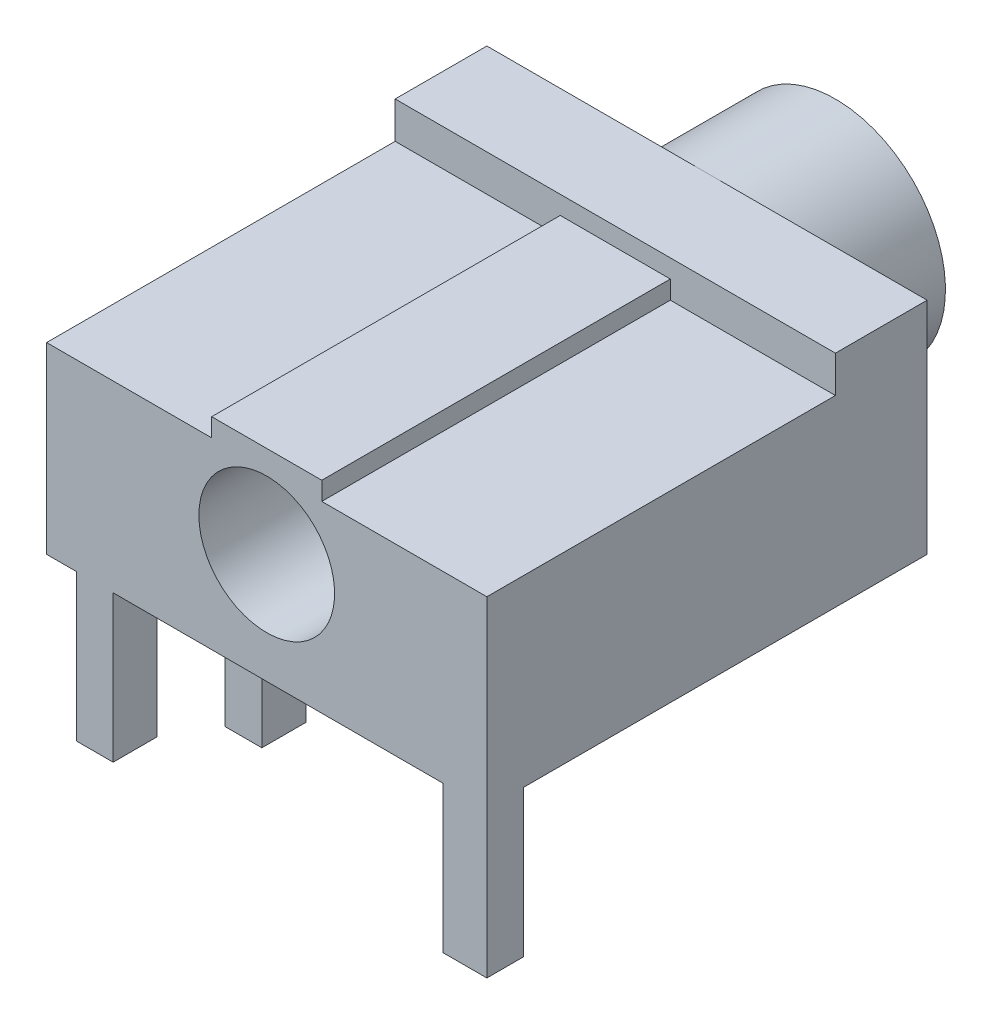
SolidWorks part; units mm, degrees
ref_plane "Plan de face" through (0, 0, 0) normal (0, 0, 1) x (1, 0, 0)
ref_plane "Plan de dessus" through (0, 0, 0) normal (0, 1, 0) x (1, 0, 0)
ref_plane "Plan de droite" through (0, 0, 0) normal (1, 0, 0) x (0, 0, -1)
sketch "Sketch1" plane through (0, 0, 0) normal (0, 1, 0) x (1, 0, 0)
  line L1 (0, 0) -> (-12, 0)
  line L2 (0, 0) -> (0, 12)
  line L3 (0, 12) -> (-12, 12)
  line L4 (-12, 0) -> (-12, 12)
  dimension "D1" = 12
  dimension "D2" = 12
extrude "Boss-Extrude1" add sketch "Sketch1" along normal blind 6
sketch "Sketch3" plane through (0, 6, 0) normal (0, 1, 0) x (1, 0, 0)
  line L0 (0, 0) -> (0, 12) construction
  line L1 (-12, 0) -> (0, 0)
  line L2 (-12, 0) -> (-12, 9.5)
  line L3 (-12, 9.5) -> (0, 9.5)
  line L4 (0, 0) -> (0, 9.5)
  line L5 (0, 12) -> (-12, 12) construction
  dimension "D1" = 2.5
extrude "Cut-Extrude1" cut sketch "Sketch3" against normal blind 1
sketch "Sketch4" plane through (0, 5, 0) normal (0, 1, 0) x (1, 0, 0)
  line L0 (-12, 0) -> (0, 0) construction
  line L1 (-7.5, 0) -> (-4.5, 0)
  line L2 (-7.5, 0) -> (-7.5, 9.5)
  line L3 (-7.5, 9.5) -> (-4.5, 9.5)
  line L4 (-4.5, 0) -> (-4.5, 9.5)
  line L5 (0, 9.5) -> (-12, 9.5) construction
  line L7 (-12, 9.5) -> (-12, 0) construction
  dimension "D1" = 3
  dimension "D2" = 4.5
extrude "Boss-Extrude2" add sketch "Sketch4" along normal blind 0.5
sketch "Sketch6" plane through (0, 0, -12) normal (0, 0, -1) x (-1, 0, 0)
  line L1 (0, 6) -> (12, 6) construction
  line L2 (0, 6) -> (0, 0) construction
  circle A0 centre (6, 3) radius 3
  dimension "D1" = 6
  dimension "D2" = 3
  dimension "D3" = 6
extrude "Boss-Extrude3" add sketch "Sketch6" along normal blind 3.5
sketch "Sketch7" plane through (0, 0, -15.5) normal (0, 0, -1) x (-1, 0, 0)
  circle A0 centre (6, 3) radius 1.85
  dimension "D1" = 3.7
extrude "Cut-Extrude2" cut sketch "Sketch7" against normal through all
sketch "Sketch8" plane through (0, 0, 0) normal (0, -1, 0) x (1, 0, 0)
  line L0 (-6, -12) -> (-12, -12) construction
  line L1 (-9.5, -12) -> (-8.3, -12)
  line L2 (-9.5, -12) -> (-9.5, -11)
  line L3 (-9.5, -11) -> (-8.3, -11)
  line L4 (-8.3, -12) -> (-8.3, -11)
  line L5 (-12, 0) -> (0, 0) construction
  line L6 (-11.1867, 0) -> (-10.1867, 0)
  line L7 (-11.1867, 0) -> (-11.1867, -1.2)
  line L8 (-11.1867, -1.2) -> (-10.1867, -1.2)
  line L9 (-10.1867, 0) -> (-10.1867, -1.2)
  line L10 (-12, -12) -> (-12, 0) construction
  line L11 (0, 0) -> (-1.2, 0)
  line L12 (0, 0) -> (0, -1)
  line L13 (0, -1) -> (-1.2, -1)
  line L14 (-1.2, 0) -> (-1.2, -1)
  line L15 (-9.5, -2.3671) -> (-8.5, -2.3671)
  line L16 (-9.5, -2.3671) -> (-9.5, -3.5671)
  line L17 (-9.5, -3.5671) -> (-8.5, -3.5671)
  line L18 (-8.5, -2.3671) -> (-8.5, -3.5671)
  dimension "D1" = 1
  dimension "D2" = 1.2
  dimension "D3" = 1
  dimension "D4" = 1.2
  dimension "D5" = 1.2
  dimension "D6" = 1
  dimension "D7" = 1
  dimension "D8" = 1.2
  dimension "D9" = 0.8133
  dimension "D10" = 2.5
  dimension "D11" = 1.1671
  dimension "D12" = 2.5
extrude "Boss-Extrude4" add sketch "Sketch8" along normal blind 4
